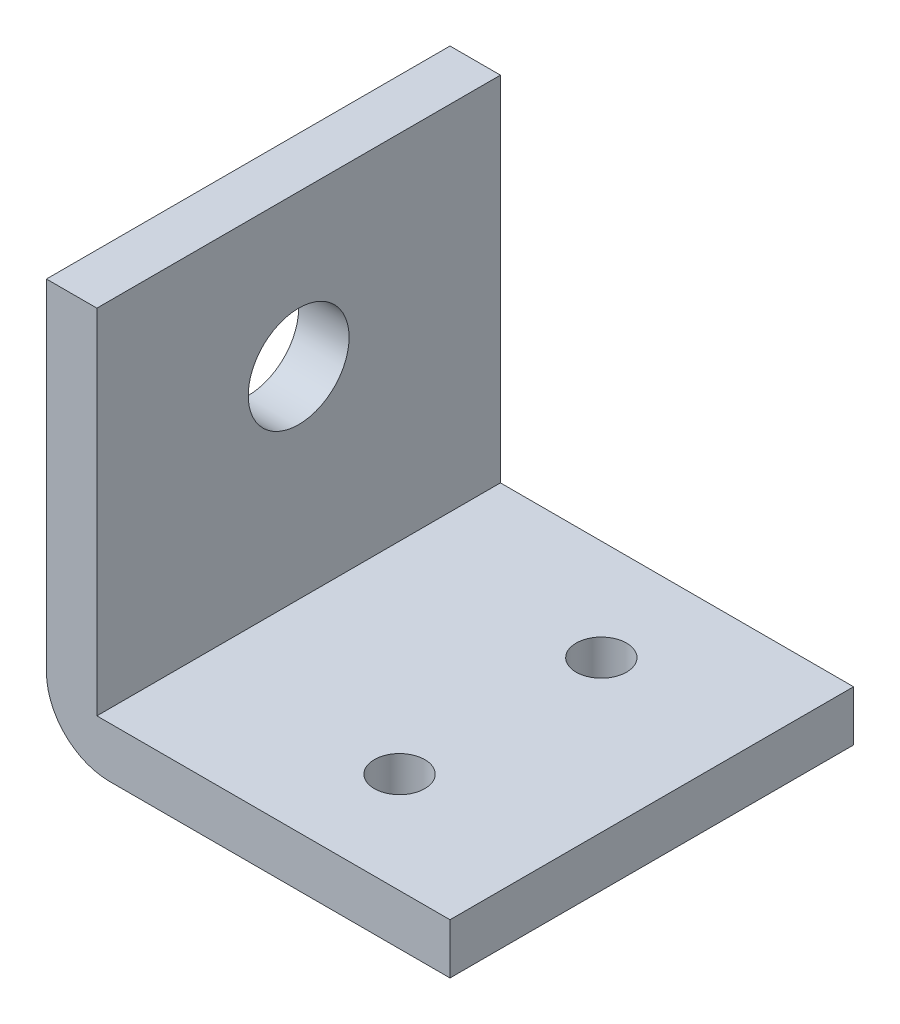
SolidWorks part; units mm, degrees
ref_plane "Front Plane" through (0, 0, 0) normal (0, 0, 1) x (1, 0, 0)
ref_plane "Top Plane" through (0, 0, 0) normal (0, 1, 0) x (1, 0, 0)
ref_plane "Right Plane" through (0, 0, 0) normal (1, 0, 0) x (0, 0, -1)
sketch "Sketch1" plane through (0, 0, 0) normal (0, 0, 1) x (1, 0, 0)
  line L2 (-35, 35) -> (-35, 0)
  line L3 (-35, 0) -> (0, 0)
  line L4 (-35, 35) -> (-40, 35)
  line L5 (-40, 35) -> (-40, 1.25)
  line L6 (-33.75, -5) -> (0, -5)
  line L7 (0, -5) -> (0, 0)
  arc A1 (-40, 1.25) -> (-33.75, -5) centre (-33.75, 1.25) ccw
  point P9 (-37.5, 35)
  dimension "D1" = 6.25
  dimension "D2" = 40
  dimension "D3" = 40
  dimension "D4" = 5
  dimension "D5" = 5
extrude "Boss-Extrude6" add sketch "Sketch1" along normal blind 40
sketch "Sketch6" plane through (-35, 0, 0) normal (1, 0, 0) x (0, 0, -1)
  circle A0 centre (-20, 20) radius 5
  dimension "D1" = 5
extrude "Cut-Extrude1" cut sketch "Sketch6" against normal through all
sketch "Sketch7" plane through (0, 0, 0) normal (0, 1, 0) x (1, 0, 0)
  circle A2 centre (-15, -10) radius 2.5
  circle A3 centre (-15, -30) radius 2.5
extrude "Cut-Extrude2" cut sketch "Sketch7" against normal through all
